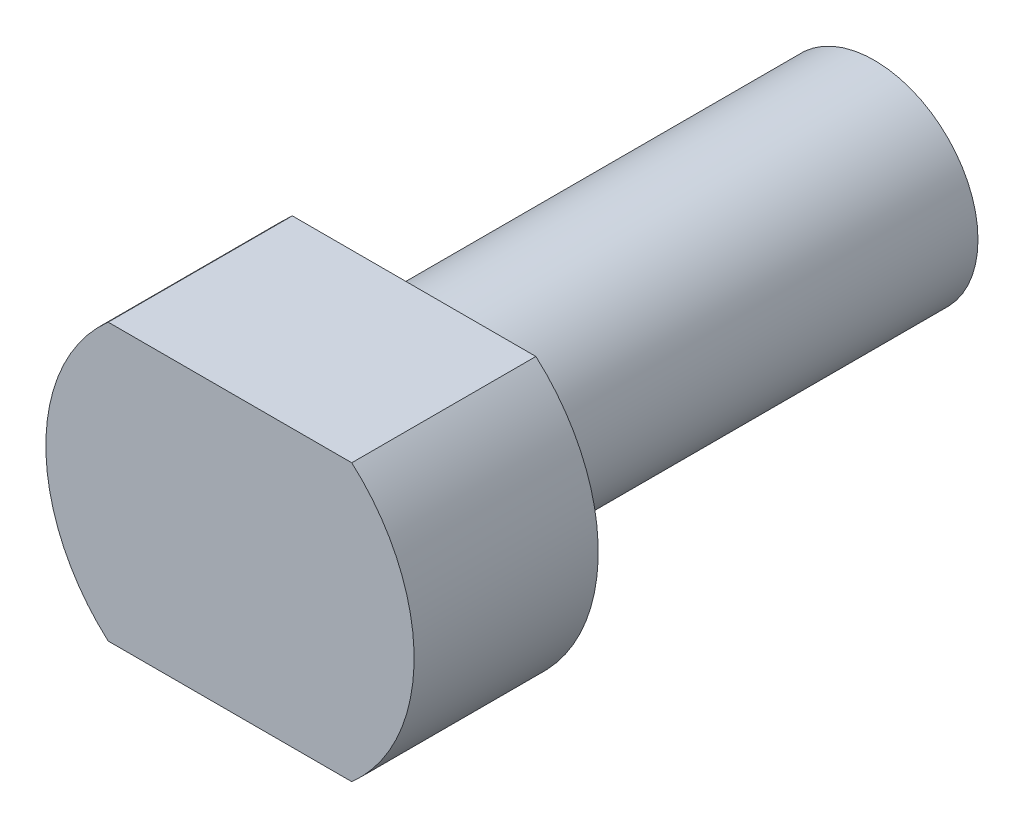
SolidWorks part; units mm, degrees
ref_plane "Front Plane" through (0, 0, 0) normal (0, 0, 1) x (1, 0, 0)
ref_plane "Top Plane" through (0, 0, 0) normal (0, 1, 0) x (1, 0, 0)
ref_plane "Right Plane" through (0, 0, 0) normal (1, 0, 0) x (0, 0, -1)
sketch "Sketch1" plane through (0, 0, 0) normal (0, 0, 1) x (1, 0, 0)
  circle A0 centre (0, 0) radius 2.25
  dimension "D1" = 4.5
extrude "Boss-Extrude1" add sketch "Sketch1" along normal blind 10 contours A0
sketch "Sketch2" plane through (0, 0, 10) normal (0, 0, 1) x (1, 0, 0)
  circle A0 centre (0, 0) radius 4
  dimension "D1" = 8
extrude "Boss-Extrude2" add sketch "Sketch2" along normal blind 4
sketch "Sketch3" plane through (0, 0, 14) normal (0, 0, 1) x (1, 0, 0)
  line L1 (-2.6458, 3) -> (2.6458, 3)
  line L3 (-2.6458, -3) -> (2.6458, -3)
  circle A0 centre (0, 0) radius 4 construction
  arc A1 (-2.6458, -3) -> (2.6458, -3) centre (0, 0) ccw
  arc A2 (2.6458, 3) -> (-2.6458, 3) centre (0, 0) ccw
  point P6 (0, 0)
  point P7 (0, 0)
  dimension "D1" = 6
extrude "Cut-Extrude1" cut sketch "Sketch3" against normal blind 4
